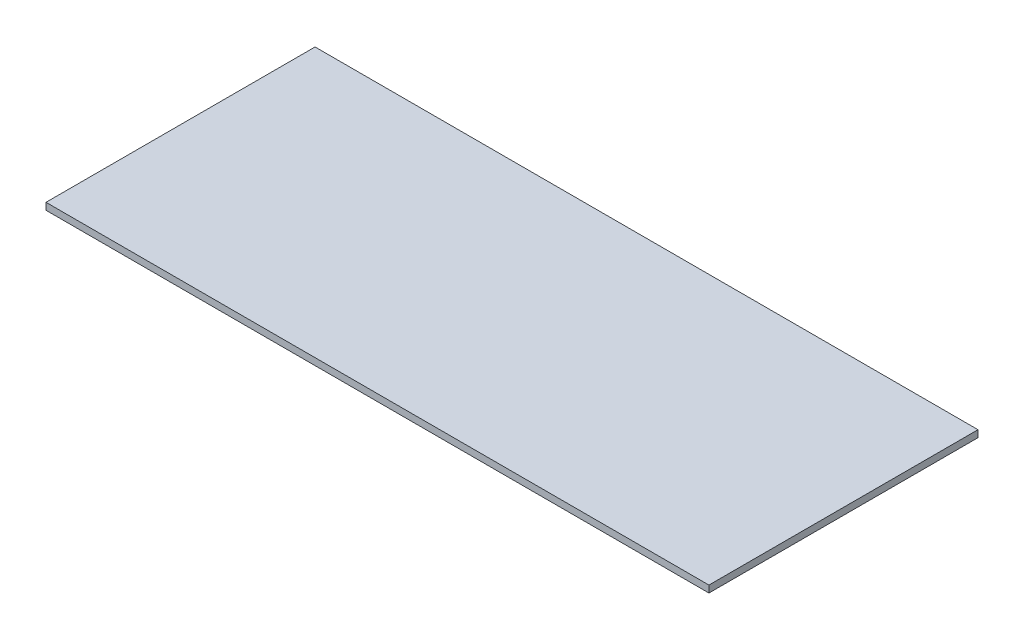
SolidWorks part; units mm, degrees
ref_plane "Front Plane" through (0, 0, 0) normal (0, 0, 1) x (1, 0, 0)
ref_plane "Top Plane" through (0, 0, 0) normal (0, 1, 0) x (1, 0, 0)
ref_plane "Right Plane" through (0, 0, 0) normal (1, 0, 0) x (0, 0, -1)
sketch "Sketch1" plane through (0, 0, 0) normal (0, 1, 0) x (1, 0, 0)
  line L1 (-59.1289, 156.3918) -> (396.1711, 156.3918)
  line L2 (-59.1289, 156.3918) -> (-59.1289, -28.4005)
  line L3 (-59.1289, -28.4005) -> (396.1711, -28.4005)
  line L4 (396.1711, 156.3918) -> (396.1711, -28.4005)
  dimension "D1" = 455.3
  dimension "D2" = 184.7924
extrude "Boss-Extrude2" add sketch "Sketch1" along normal blind 4.7625
